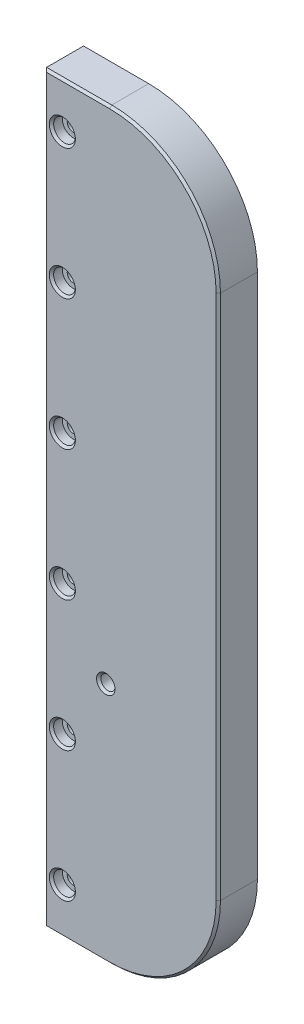
SolidWorks part; units mm, degrees
ref_plane "Front Plane" through (0, 0, 0) normal (0, 0, 1) x (1, 0, 0)
ref_plane "Top Plane" through (0, 0, 0) normal (0, 1, 0) x (1, 0, 0)
ref_plane "Right Plane" through (0, 0, 0) normal (1, 0, 0) x (0, 0, -1)
sketch "Sketch1" plane through (0, 0, 0) normal (0, 0, 1) x (1, 0, 0)
  line L1 (1, 271) -> (81, 271)
  line L2 (1, 271) -> (1, -71)
  line L3 (1, -71) -> (81, -71)
  line L4 (81, 271) -> (81, -71)
  dimension "D1" = 342
  dimension "D2" = 80
extrude "Boss-Extrude1" add sketch "Sketch1" along normal blind 18
fillet "Fillet1" radius 50 2 edges at (81, 271, 9) (81, -71, 9)
sketch "Sketch2" plane through (0, 0, 18) normal (0, 0, 1) x (1, 0, 0)
  circle A0 centre (9.25, -50) radius 2.5
  circle A1 centre (9.25, 10) radius 2.5
  circle A2 centre (9.25, 70) radius 2.5
  circle A3 centre (9.25, 130) radius 2.5
  circle A4 centre (9.25, 190) radius 2.5
  circle A5 centre (9.25, 250) radius 2.5
  point P0 (0, -80)
  dimension "D1" = 6
hole_wizard "CBORE for M5 SHCS1" positions "Sketch3" profile "Sketch4" counterbore size "M5" standard "ANSI Metric"
sketch "Sketch3" plane through (0, 0, 18) normal (0, 0, 1) x (1, 0, 0)
  point P0 (9.25, 250)
  point P3 (9.25, 190)
  point P6 (9.25, 130)
  point P9 (9.25, 70)
  point P12 (9.25, 10)
  point P15 (9.25, -50)
sketch "Sketch4" plane through (9.25, 250, 18) normal (1, 0, 0) x (0, -1, 0)
  line L0 (0, 0) -> (0, 30)
  line L1 (0, 30) -> (2.75, 28.3476)
  line L2 (2.75, 28.3476) -> (2.75, 5)
  line L3 (2.75, 5) -> (5, 5)
  line L4 (5, 5) -> (5, 0)
  line L5 (5, 0) -> (0, 0)
  line L10 (0, 30) -> (-2.75, 28.3476) construction
  line L11 (0, -6.35) -> (0, 107.95) construction
  dimension "Hole Dia." = 5.5
  dimension "Hole Depth" = 30
  dimension "C'Bore Dia." = 10
  dimension "C'Bore Depth" = 5
  dimension "Drill Angle" = 118
chamfer "Chamfer1" distance 1 angle 45 12 edges at (66.3553, -56.3553, 18) (16, -71, 18) (1, 100, 18) (16, 271, 18) (66.3553, 256.3553, 18) (81, 100, 18) (14.25, -50, 18) (14.25, 10, 18) (14.25, 70, 18) (14.25, 130, 18) (14.25, 190, 18) (14.25, 250, 18)
sketch "Sketch5" plane through (0, 0, 18) normal (0, 0, 1) x (1, 0, 0)
  circle A0 centre (29.25, 40) radius 3.25
extrude "Cut-Extrude1" cut sketch "Sketch5" against normal through all
chamfer "Chamfer2" distance 1 angle 45 2 edges at (32.5, 40, 0) (32.5, 40, 18)
